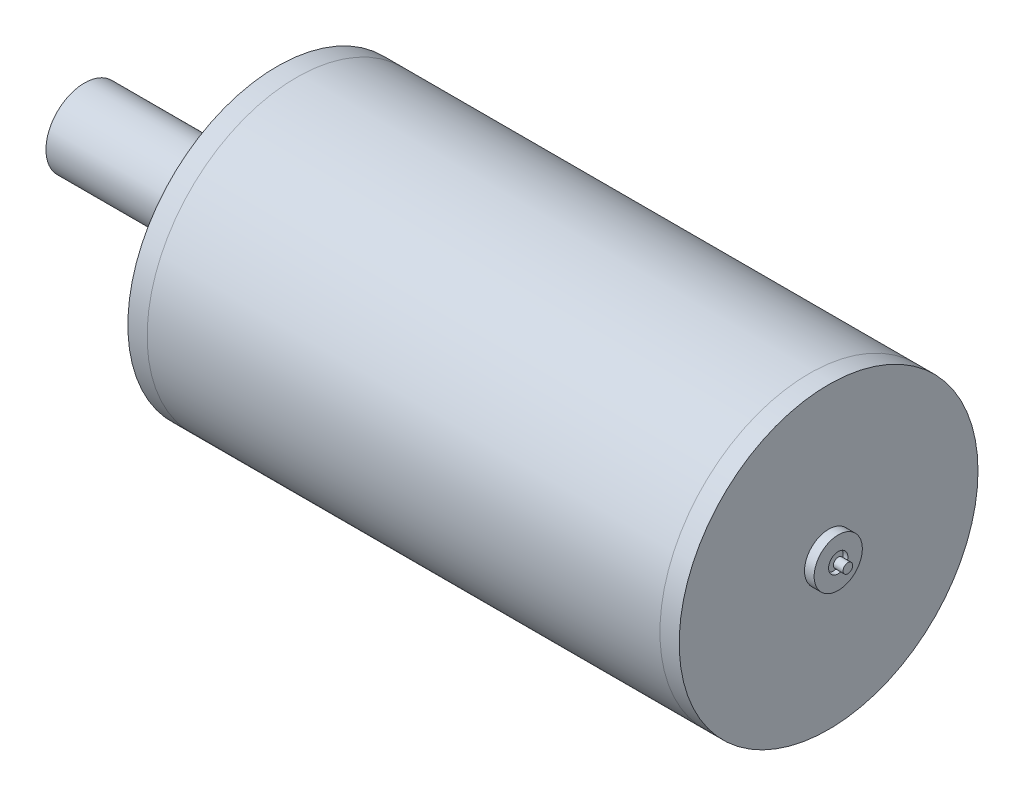
SolidWorks part; units mm, degrees
ref_plane "Alzado" through (0, 0, 0) normal (0, 0, 1) x (1, 0, 0)
ref_plane "Planta" through (0, 0, 0) normal (0, 1, 0) x (1, 0, 0)
ref_plane "Vista lateral" through (0, 0, 0) normal (1, 0, 0) x (0, 0, -1)
sketch "Croquis2" plane through (0, 0, 0) normal (1, 0, 0) x (0, 0, -1)
  circle A0 centre (0, 0) radius 15.5
  dimension "D1" = 31
extrude "Saliente-Extruir1" add sketch "Croquis2" along normal blind 2
sketch "Croquis3" plane through (2, 0, 0) normal (1, 0, 0) x (0, 0, -1)
  circle A0 centre (0, 0) radius 15.5
  dimension "D1" = 31
extrude "Saliente-Extruir2" add sketch "Croquis3" along normal blind 53.2 separate body contours A0
sketch "Croquis4" plane through (55.2, 0, 0) normal (1, 0, 0) x (0, 0, -1)
  circle A0 centre (0, 0) radius 15.5
extrude "Saliente-Extruir3" add sketch "Croquis4" along normal blind 2
sketch "Croquis5" plane through (57.2, 0, 0) normal (1, 0, 0) x (0, 0, -1)
  circle A0 centre (0, 0) radius 2.5
  dimension "D1" = 5
extrude "Saliente-Extruir4" add sketch "Croquis5" along normal blind 1
sketch "Croquis6" plane through (58.2, 0, 0) normal (1, 0, 0) x (0, 0, -1)
  circle A0 centre (0, 0) radius 0.5
  dimension "D1" = 1
extrude "Saliente-Extruir5" add sketch "Croquis6" along normal blind 1
sketch "Croquis8" plane through (0, 0, 0) normal (1, 0, 0) x (0, 0, -1)
  circle A0 centre (0, 0) radius 4
  dimension "D1" = 8
extrude "Saliente-Extruir6" add sketch "Croquis8" against normal blind 20
sketch "Croquis9" plane through (58.2, 0, 0) normal (1, 0, 0) x (0, 0, -1)
  circle A0 centre (0, 0) radius 0.4961
  circle A1 centre (0, 0) radius 1
  dimension "D1" = 2
extrude "Cortar-Extruir4" cut sketch "Croquis9" against normal blind 0.5 contours A1
